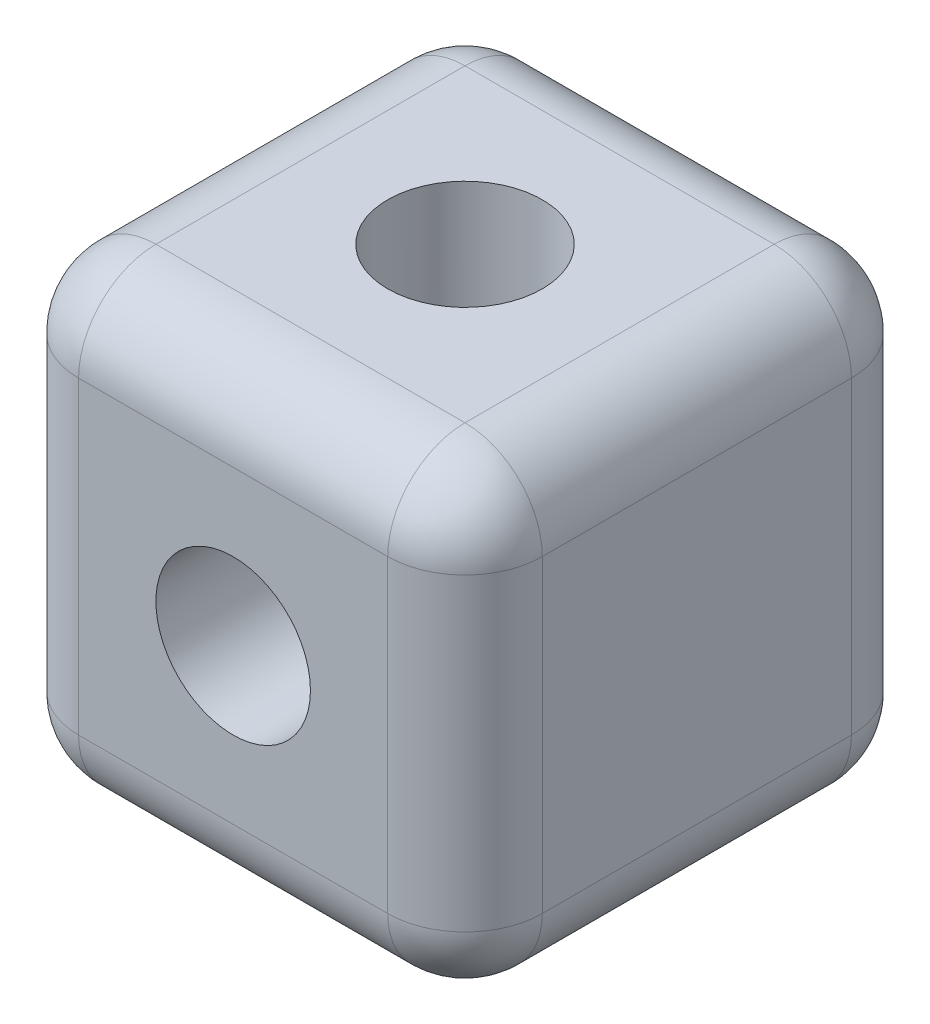
SolidWorks part; units mm, degrees
ref_plane "Front Plane" through (0, 0, 0) normal (0, 0, 1) x (1, 0, 0)
ref_plane "Top Plane" through (0, 0, 0) normal (0, 1, 0) x (1, 0, 0)
ref_plane "Right Plane" through (0, 0, 0) normal (1, 0, 0) x (0, 0, -1)
sketch "Sketch3" plane through (0, 0, 0) normal (0, 1, 0) x (1, 0, 0)
  line L1 (-3, -3) -> (3, -3)
  line L2 (-3, -3) -> (-3, 3)
  line L3 (-3, 3) -> (3, 3)
  line L4 (3, -3) -> (3, 3)
  line L5 (-3, -3) -> (3, 3) construction
  line L6 (-3, 3) -> (3, -3) construction
  point P0 (0, 0)
  dimension "D1" = 6
  dimension "D2" = 6
extrude "Boss-Extrude1" add sketch "Sketch3" along normal blind 6
sketch "Sketch4" plane through (0, 0, 3) normal (0, 0, 1) x (1, 0, 0)
  line L0 (-3, 3) -> (3, 3) construction
  line L1 (-3, 6) -> (-3, 0) construction
  line L2 (3, 6) -> (3, 0) construction
  circle A0 centre (0, 3) radius 1
  dimension "D1" = 2
extrude "Cut-Extrude1" cut sketch "Sketch4" against normal up to surface (6 mm away) up to face at (0, 3, -3)
sketch "Sketch5" plane through (0, 6, 0) normal (0, 1, 0) x (1, 0, 0)
  line L0 (-3, 0) -> (3, 0) construction
  line L1 (-3, 3) -> (-3, -3) construction
  line L2 (3, -3) -> (3, 3) construction
  line L3 (0, -3) -> (0, 3) construction
  line L4 (-3, -3) -> (3, -3) construction
  line L5 (3, 3) -> (-3, 3) construction
  circle A0 centre (0, 0) radius 1
  dimension "D1" = 2
extrude "Cut-Extrude2" cut sketch "Sketch5" against normal up to surface (6 mm away) up to face at (0, 0, 0)
fillet "Fillet1" radius 1 12 edges at (-3, 3, 3) (-3, 0, 0) (0, 0, -3) (3, 0, 0) (0, 0, 3) (3, 3, 3) (3, 3, -3) (-3, 3, -3) (0, 6, -3) (-3, 6, 0) (0, 6, 3) (3, 6, 0)
